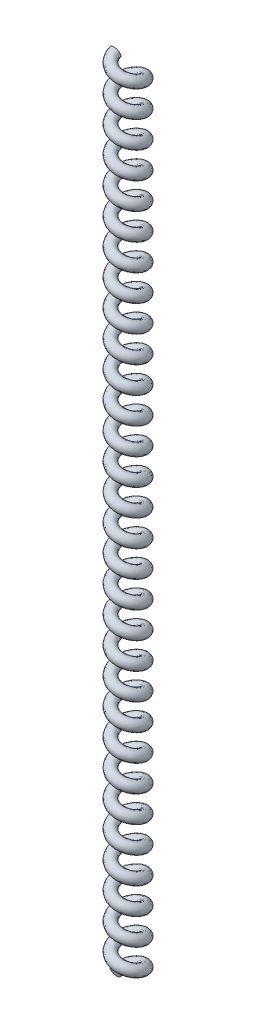
SolidWorks part; units mm, degrees
ref_plane "Front" through (0, 0, 0) normal (0, 0, 1) x (1, 0, 0)
ref_plane "Top" through (0, 0, 0) normal (0, 1, 0) x (1, 0, 0)
ref_plane "Right" through (0, 0, 0) normal (1, 0, 0) x (0, 0, -1)
sketch "Sketch2" plane through (0, 0, 0) normal (0, 1, 0) x (1, 0, 0)
  circle A0 centre (0, 0) radius 2.5
  dimension "D1" = 5
curve "Helix/Spiral1" pitch 5 height 150 turns 30
ref_plane "Plane1" through (-2.5, 150, 0) normal (0, 0.3033, -0.9529) x (-1, 0, 0)
sketch "Sketch3" plane through (-2.5, 150, 0) normal (0, 0.3033, -0.9529) x (-1, 0, 0)
  circle A0 centre (-0.1648, 0.1399) radius 1
  dimension "D1" = 2
sweep "Sweep1" add profiles "Sketch3" path "Helix/Spiral1"
